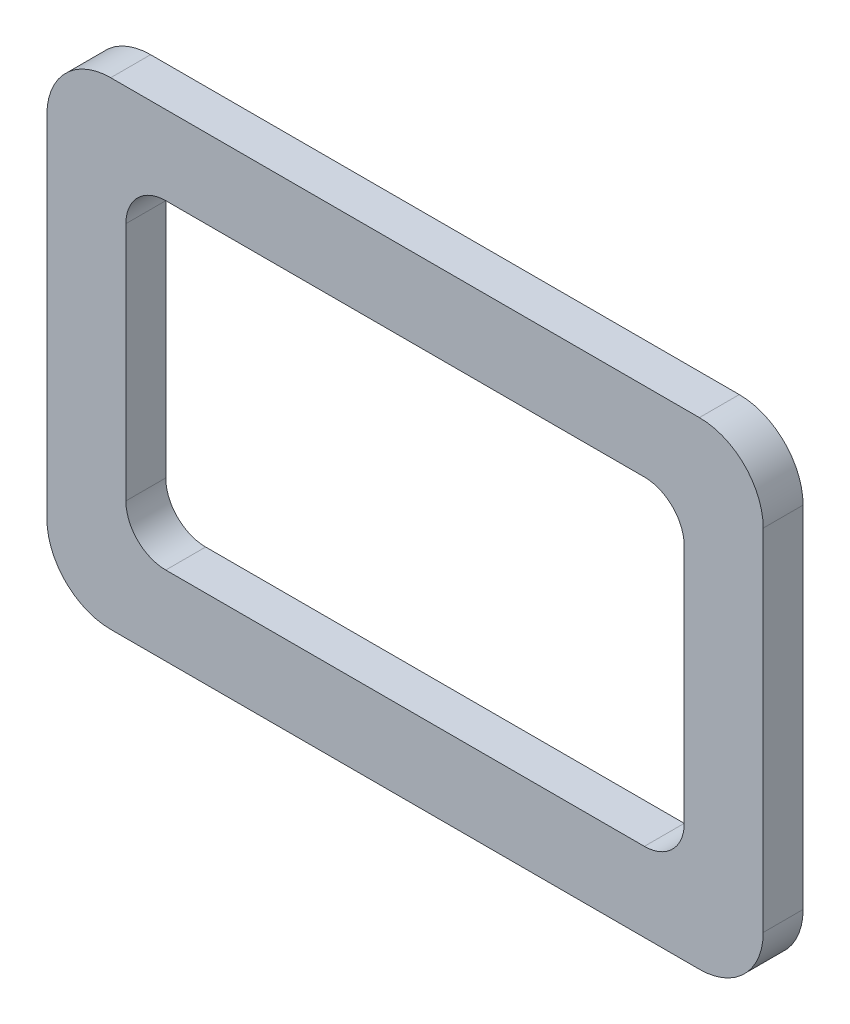
SolidWorks part; units mm, degrees
ref_plane "Alzado" through (0, 0, 0) normal (0, 0, 1) x (1, 0, 0)
ref_plane "Planta" through (0, 0, 0) normal (0, 1, 0) x (1, 0, 0)
ref_plane "Vista lateral" through (0, 0, 0) normal (1, 0, 0) x (0, 0, -1)
sketch "Sketch1" plane through (0, 0, 0) normal (0, 0, 1) x (1, 0, 0)
  line L0 (49.5119, -13.6489) -> (4.6119, -13.6489)
  line L1 (49.5119, -13.6489) -> (49.5119, -3.7489)
  line L2 (49.5119, 46.2511) -> (4.6119, 46.2511)
  line L3 (4.6119, -13.6489) -> (4.6119, 46.2511)
  line L4 (49.5119, 36.3511) -> (49.5119, 46.2511)
  line L5 (49.5119, -3.7489) -> (14.5119, -3.7489)
  line L6 (49.5119, 36.3511) -> (14.5119, 36.3511)
  line L7 (14.5119, -3.7489) -> (14.5119, 36.3511)
  dimension "D1" = 9.9
  dimension "D2" = 9.9
  dimension "D3" = 9.9
  dimension "D4" = 44.9
  dimension "D5" = 59.9
extrude "Boss-Extrude1" add sketch "Sketch1" along normal blind 5
ref_plane "Plane1" through (49.5119, 0, 0) normal (1, 0, 0) x (0, 0, -1)
mirror "Mirror1" about plane through (49.5119, 0, 0) normal (1, 0, 0) of "Boss-Extrude1"
fillet "Fillet1" radius 8 4 edges at (4.6119, -13.6489, 2.5) (4.6119, 46.2511, 2.5) (94.4119, 46.2511, 2.5) (94.4119, -13.6489, 2.5)
fillet "Fillet3" radius 5 4 edges at (84.5119, -3.7489, 2.5) (84.5119, 36.3511, 2.5) (14.5119, -3.7489, 2.5) (14.5119, 36.3511, 2.5)
